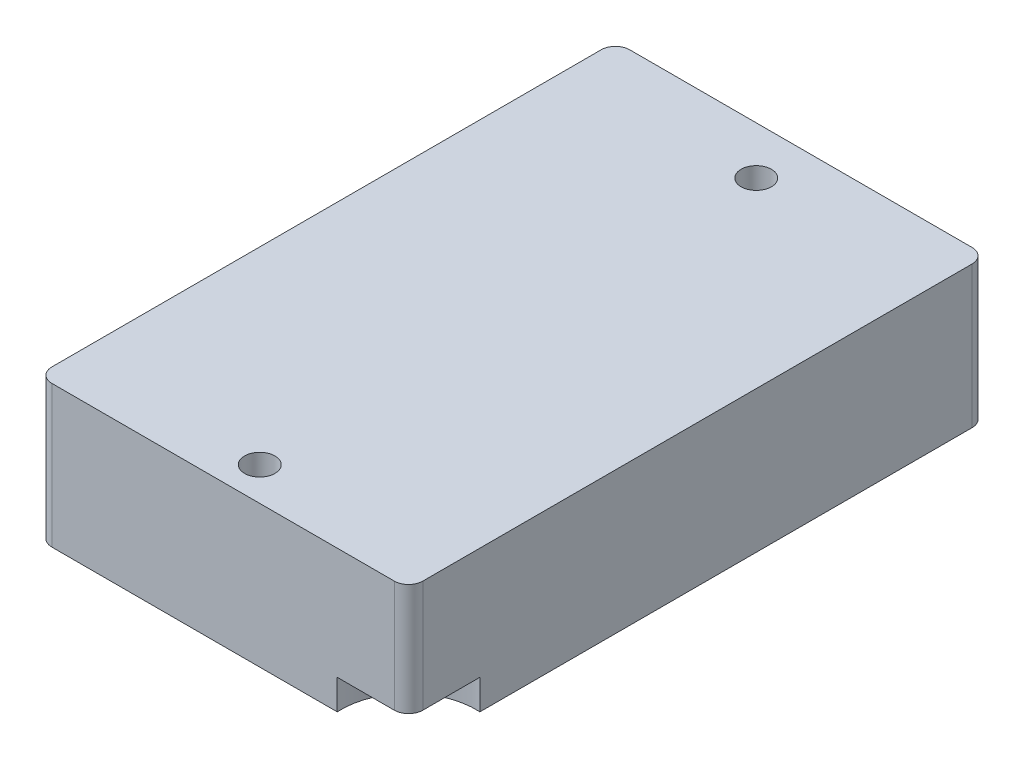
SolidWorks part; units mm, degrees
ref_plane "Front Plane" through (0, 0, 0) normal (0, 0, 1) x (1, 0, 0)
ref_plane "Top Plane" through (0, 0, 0) normal (0, 1, 0) x (1, 0, 0)
ref_plane "Right Plane" through (0, 0, 0) normal (1, 0, 0) x (0, 0, -1)
sketch "Sketch1" plane through (0, 0, 0) normal (0, 1, 0) x (1, 0, 0)
  line L1 (0, 0) -> (66.04, 0)
  line L2 (0, 0) -> (0, 102.87)
  line L3 (0, 102.87) -> (66.04, 102.87)
  line L4 (66.04, 0) -> (66.04, 102.87)
  dimension "D1" = 66.04
  dimension "D2" = 102.87
extrude "Extrude1" add sketch "Sketch1" along normal blind 25.2476
fillet "Fillet1" radius 2.54 4 edges at (0, 12.6238, -102.87) (66.04, 12.6238, -102.87) (66.04, 12.6238, 0) (0, 12.6238, 0)
sketch "Sketch2" plane through (0, 0, 0) normal (0, -1, 0) x (1, 0, 0)
  line L0 (66.04, -2.54) -> (66.04, -100.33) construction
  line L1 (2.54, 0) -> (63.5, 0) construction
  circle A0 centre (56.1848, -20.955) radius 0.3175
  circle A1 centre (58.7248, -20.955) radius 0.3175
  dimension "D1" = 0.635
  dimension "D2" = 2.54
  dimension "D3" = 7.3152
  dimension "D4" = 20.955
extrude "Extrude2" add sketch "Sketch2" along normal blind 5.334
pattern_linear "LPattern1" count 25 spacing 2.54 along (0, 0, -1) of "Extrude2"
sketch "Sketch3" plane through (0, 0, 0) normal (0, -1, 0) x (1, 0, 0)
  circle A0 centre (8.4328, -69.215) radius 0.3175
  circle A1 centre (10.9728, -69.215) radius 0.3175
  circle A3 centre (58.7248, -81.915) radius 0.3175 construction
  dimension "D1" = 0.635
  dimension "D2" = 47.752
  dimension "D3" = 2.54
  dimension "D4" = 12.7
extrude "Extrude3" add sketch "Sketch3" along normal blind 5.334
pattern_linear "LPattern2" count 16 spacing 2.54 along (0, 0, 1) of "Extrude3"
sketch "Sketch4" plane through (0, 0, 0) normal (0, -1, 0) x (1, 0, 0)
  line L0 (2.54, 0) -> (63.5, 0) construction
  line L1 (66.04, -2.54) -> (66.04, -100.33) construction
  line L2 (0, -100.33) -> (0, -2.54) construction
  line L3 (63.5, -102.87) -> (2.54, -102.87) construction
  line L4 (53.34, 0) -> (63.5, 0)
  line L5 (66.04, -2.54) -> (66.04, -12.7)
  line L6 (12.7, -102.87) -> (2.54, -102.87)
  line L7 (0, -100.33) -> (0, -90.17)
  arc A0 (53.34, 0) -> (66.04, -12.7) centre (65.3334, -0.7066) ccw
  arc A1 (0, -90.17) -> (12.7, -102.87) centre (0.7198, -102.1502) cw
  arc A2 (66.04, -2.54) -> (63.5, 0) centre (63.5, -2.54) ccw construction
  arc A3 (66.04, -2.54) -> (63.5, 0) centre (63.5, -2.54) ccw
  arc A4 (0, -100.33) -> (2.54, -102.87) centre (2.54, -100.33) ccw construction
  arc A5 (0, -100.33) -> (2.54, -102.87) centre (2.54, -100.33) ccw
  dimension "D1" = 12.7
  dimension "D4" = 12.0018
  dimension "D3" = 12.0142
  dimension "D2" = 12.7
  dimension "D5" = 12.7
  dimension "D6" = 12.7
extrude "Cut-Extrude1" cut sketch "Sketch4" against normal blind 5.334
sketch "Sketch5" plane through (0, 0, 0) normal (0, -1, 0) x (1, 0, 0)
  circle A0 centre (33.5788, -5.969) radius 2.7051
  circle A1 centre (33.5788, -94.361) radius 2.7051
  circle A2 centre (58.7248, -20.955) radius 0.3175 construction
  circle A3 centre (58.7248, -81.915) radius 0.3175 construction
  dimension "D1" = 25.146
  dimension "D2" = 12.446
  dimension "D3" = 75.946
  dimension "D4" = 25.146
  dimension "D5" = 5.4102
  dimension "D6" = 5.4102
extrude "Cut-Extrude2" cut sketch "Sketch5" against normal blind 25.654
